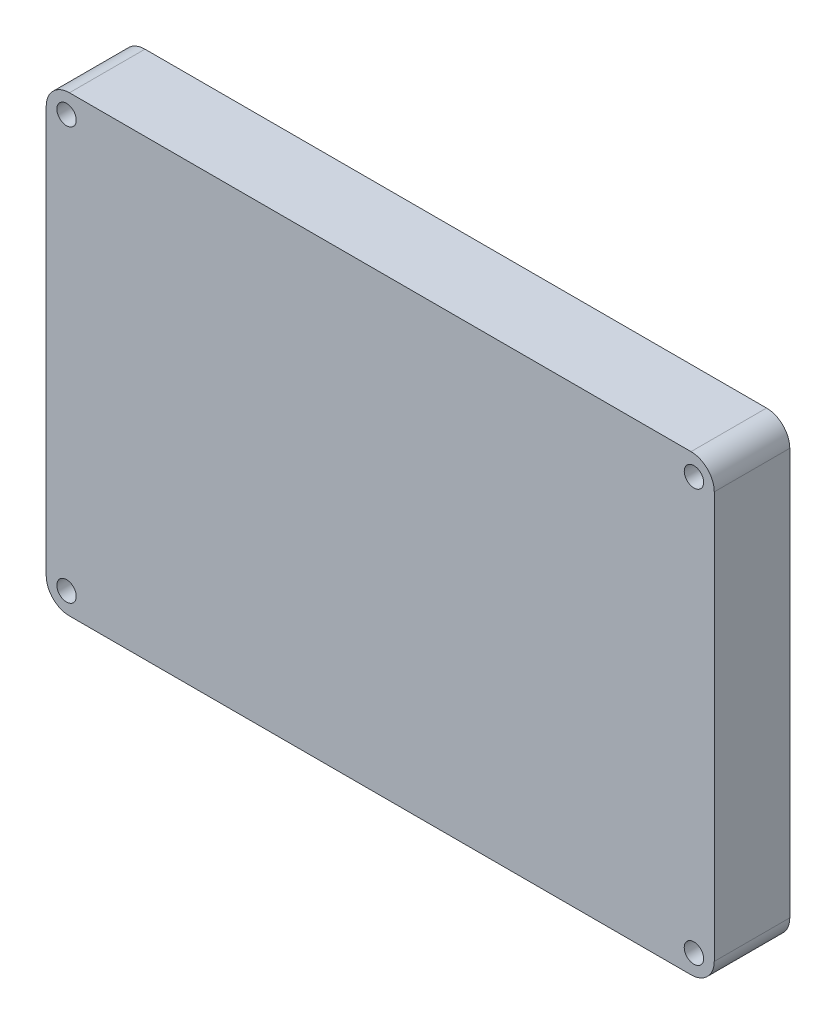
SolidWorks part; units mm, degrees
ref_plane "Front Plane" through (0, 0, 0) normal (0, 0, 1) x (1, 0, 0)
ref_plane "Top Plane" through (0, 0, 0) normal (0, 1, 0) x (1, 0, 0)
ref_plane "Right Plane" through (0, 0, 0) normal (1, 0, 0) x (0, 0, -1)
sketch "Sketch1" plane through (0, 0, 0) normal (0, 0, 1) x (1, 0, 0)
  line L0 (-57.5, 96.6651) -> (-57.5, -39.5687) construction
  line L1 (-115, 78) -> (0, 78)
  line L2 (-115, 78) -> (-115, 0)
  line L3 (-115, 0) -> (0, 0)
  line L4 (0, 78) -> (0, 0)
  line L5 (-154.968, 39) -> (66.7715, 39) construction
  circle A0 centre (-111.5, 74.5) radius 1.67
  circle A1 centre (-3.5, 74.5) radius 1.67
  circle A2 centre (-3.5, 3.5) radius 1.67
  circle A3 centre (-111.5, 3.5) radius 1.67
  point P7 (-57.5, 78)
  point P10 (-115, 39)
  dimension "D4" = 35.5
  dimension "D1" = 78
  dimension "D2" = 115
  dimension "D3" = 54
extrude "Boss-Extrude1" add sketch "Sketch1" along normal blind 13
fillet "Fillet1" radius 4 4 edges at (-115, 0, 6.5) (0, 0, 6.5) (0, 78, 6.5) (-115, 78, 6.5)
